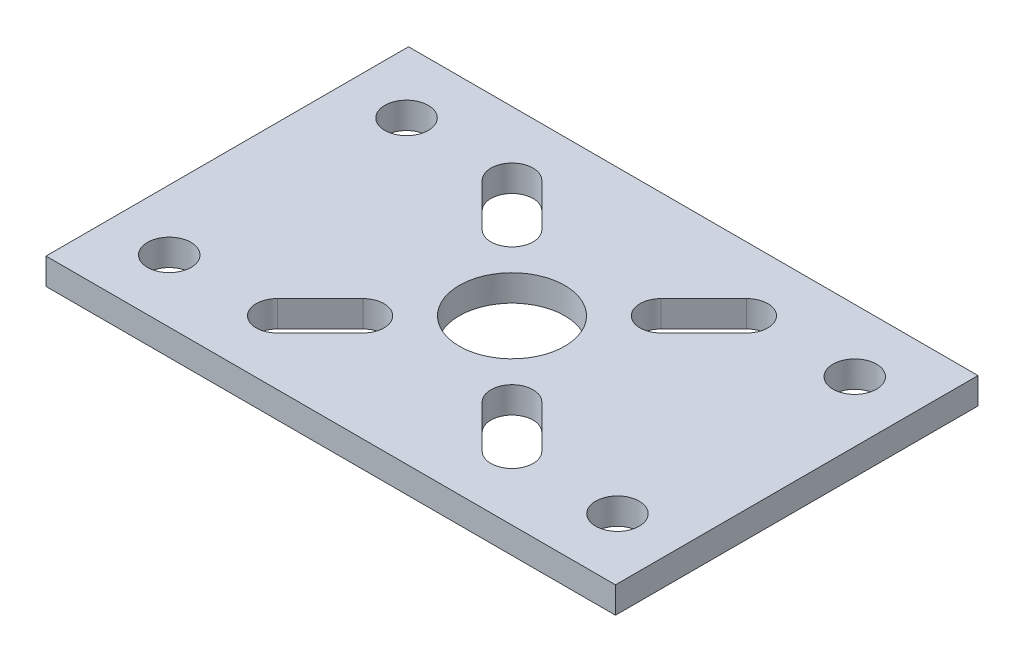
SolidWorks part; units mm, degrees
ref_plane "前视基准面" through (0, 0, 0) normal (0, 0, 1) x (1, 0, 0)
ref_plane "上视基准面" through (0, 0, 0) normal (0, 1, 0) x (1, 0, 0)
ref_plane "右视基准面" through (0, 0, 0) normal (1, 0, 0) x (0, 0, -1)
sketch "草图1" plane through (0, 0, 0) normal (0, 1, 0) x (1, 0, 0)
  line L1 (-21.6, -13.75) -> (21.6, -13.75)
  line L2 (-21.6, -13.75) -> (-21.6, 13.75)
  line L3 (-21.6, 13.75) -> (21.6, 13.75)
  line L4 (21.6, -13.75) -> (21.6, 13.75)
  line L5 (-21.6, -13.75) -> (21.6, 13.75) construction
  line L6 (-21.6, 13.75) -> (21.6, -13.75) construction
  point P0 (0, 0)
  dimension "D1" = 27.5
  dimension "D2" = 43.2
extrude "凸台-拉伸1" add sketch "草图1" along normal blind 2
sketch "草图2" plane through (0, 2, 0) normal (0, 1, 0) x (1, 0, 0)
  line L1 (17, -9) -> (-17, -9) construction
  line L2 (17, -9) -> (17, 9) construction
  line L3 (17, 9) -> (-17, 9) construction
  line L4 (-17, -9) -> (-17, 9) construction
  line L5 (17, -9) -> (-17, 9) construction
  line L6 (17, 9) -> (-17, -9) construction
  circle A0 centre (-17, 9) radius 1.65
  point P0 (0, 0)
  dimension "D3" = 3.3
  dimension "D1" = 34
  dimension "D2" = 18
extrude "切除-拉伸1" cut sketch "草图2" against normal up to next
sketch "草图3" plane through (0, 2, 0) normal (0, 1, 0) x (1, 0, 0)
  line L0 (0, 13.75) -> (0, -13.75) construction
  line L1 (21.6, 13.75) -> (-21.6, 13.75) construction
  line L2 (-21.6, -13.75) -> (21.6, -13.75) construction
  line L3 (0, 0) -> (-5.6569, 5.6569) construction
  line L4 (-5.6569, 5.6569) -> (-8.9025, 8.9025) construction
  line L5 (-6.7882, 4.5255) -> (-10.0338, 7.7711)
  line L6 (-4.5255, 6.7882) -> (-7.7711, 10.0338)
  arc A0 (-6.7882, 4.5255) -> (-4.5255, 6.7882) centre (-5.6569, 5.6569) ccw
  arc A1 (-7.7711, 10.0338) -> (-10.0338, 7.7711) centre (-8.9025, 8.9025) ccw
  point P9 (-7.2797, 7.2797)
  dimension "D4" = 1.6
  dimension "D1" = 45
  dimension "D2" = 8
  dimension "D3" = 4.59
extrude "切除-拉伸2" cut sketch "草图3" against normal up to next
mirror "镜向1" about plane through (0, 0, 0) normal (0, 0, 1) of "切除-拉伸2", "切除-拉伸1"
mirror "镜向2" about plane through (0, 0, 0) normal (1, 0, 0) of "镜向1", "切除-拉伸1", "切除-拉伸2"
sketch "草图4" plane through (0, 2, 0) normal (0, 1, 0) x (1, 0, 0)
  circle A0 centre (0, 0) radius 4
  dimension "D1" = 8
extrude "切除-拉伸3" cut sketch "草图4" against normal up to next
